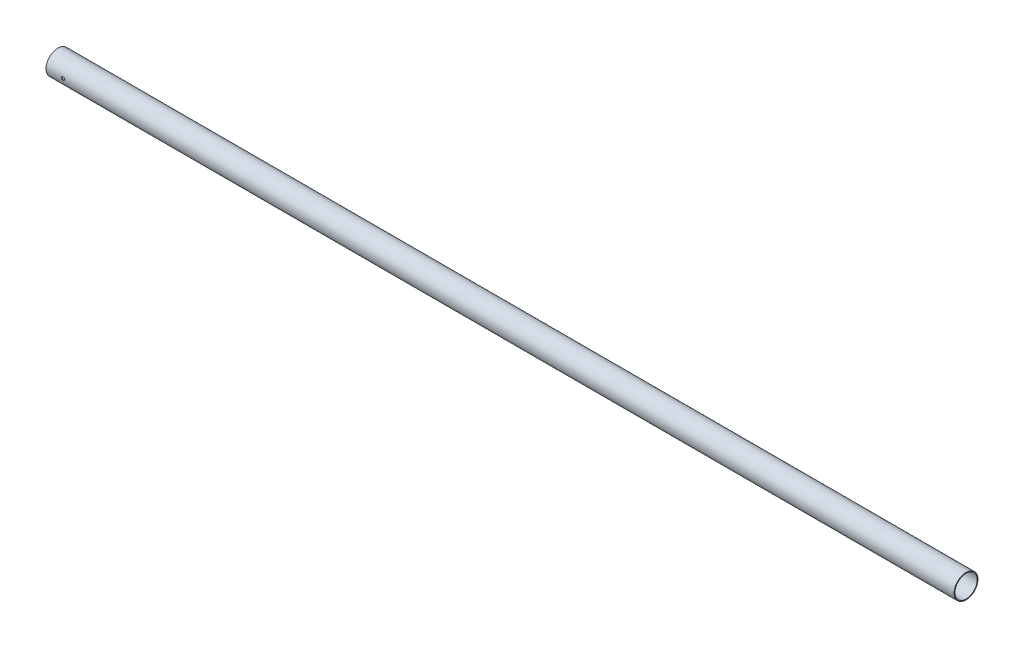
SolidWorks part; units mm, degrees
ref_plane "Front Plane" through (0, 0, 0) normal (0, 0, 1) x (1, 0, 0)
ref_plane "Top Plane" through (0, 0, 0) normal (0, 1, 0) x (1, 0, 0)
ref_plane "Right Plane" through (0, 0, 0) normal (1, 0, 0) x (0, 0, -1)
sketch "Sketch1" plane through (0, 0, 0) normal (1, 0, 0) x (0, 0, -1)
  circle A0 centre (0, 0) radius 12.7
  circle A1 centre (0, 0) radius 11.811
extrude "Boss-Extrude1" add sketch "Sketch1" along normal blind 965.67
sketch "Sketch2" plane through (0, 0, 0) normal (0, 0, 1) x (1, 0, 0)
  circle A0 centre (18, 0) radius 1.7
extrude "Cut-Extrude1" cut sketch "Sketch2" against normal through all and the other way through all
